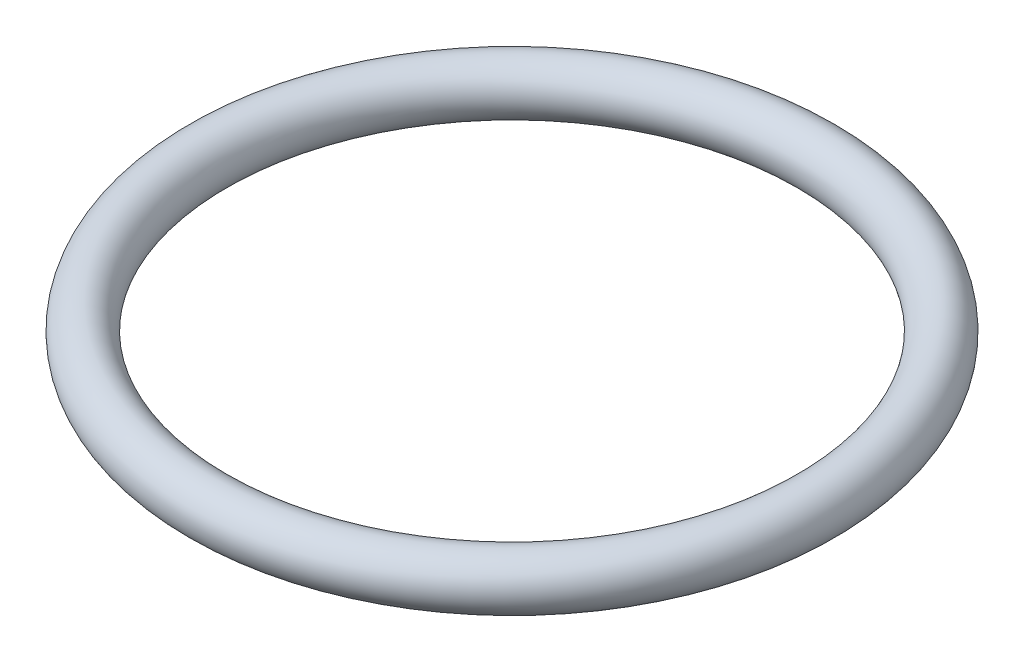
SolidWorks part; units mm, degrees
ref_plane "Płaszczyzna przednia" through (0, 0, 0) normal (0, 0, 1) x (1, 0, 0)
ref_plane "Płaszczyzna górna" through (0, 0, 0) normal (0, 1, 0) x (1, 0, 0)
ref_plane "Płaszczyzna prawa" through (0, 0, 0) normal (1, 0, 0) x (0, 0, -1)
sketch "Szkic1" plane through (0, 0, 0) normal (0, 0, 1) x (1, 0, 0)
  line L0 (0, 5.1245) -> (0, -7.9044) construction
  circle A0 centre (-17.5, -1.39) radius 1.5
  dimension "D1" = 3
  dimension "D2" = 17.5
revolve "Obrót1" add sketch "Szkic1" angle 360 about L0
